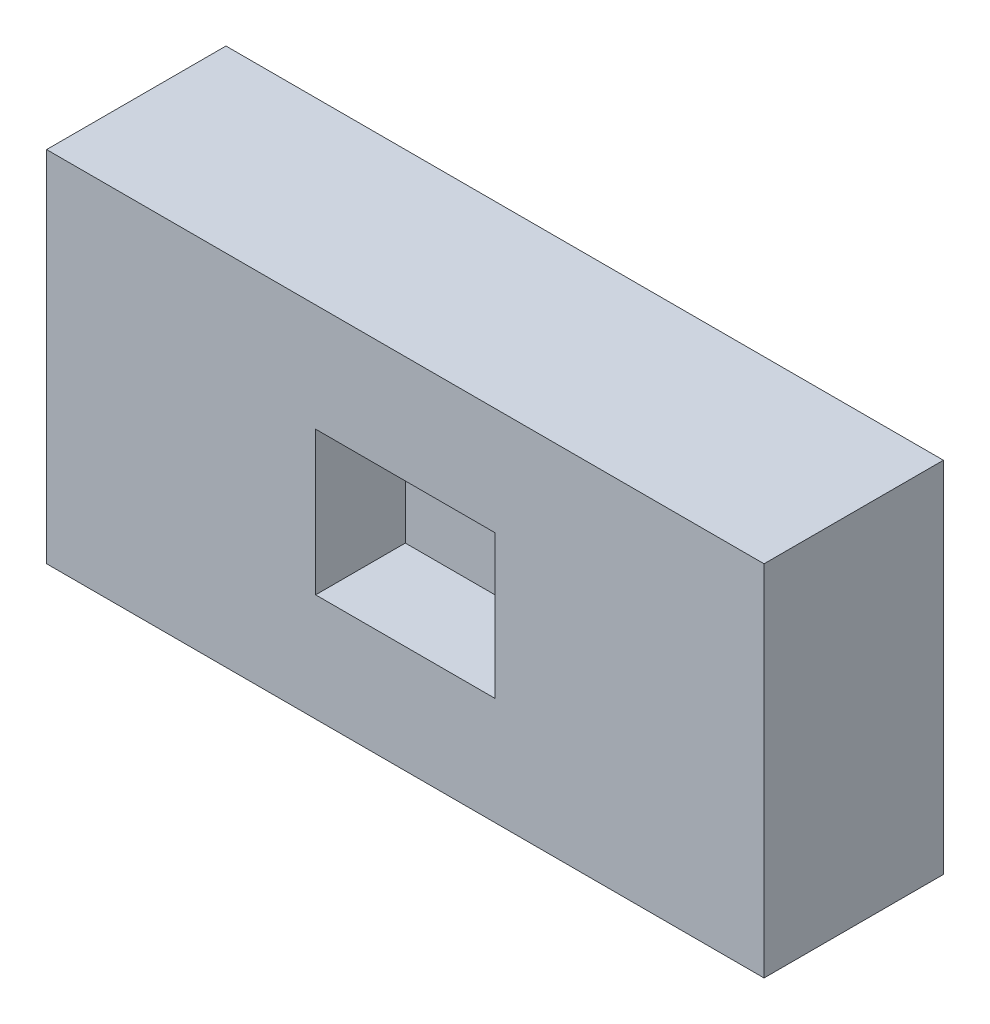
SolidWorks part; units mm, degrees
ref_plane "Front Plane" through (0, 0, 0) normal (0, 0, 1) x (1, 0, 0)
ref_plane "Top Plane" through (0, 0, 0) normal (0, 1, 0) x (1, 0, 0)
ref_plane "Right Plane" through (0, 0, 0) normal (1, 0, 0) x (0, 0, -1)
sketch "RectangleSketch" plane through (0, 0, 0) normal (0, 0, 1) x (1, 0, 0)
  line L1 (0, 0) -> (40, 0)
  line L2 (0, 0) -> (0, 20)
  line L3 (0, 20) -> (40, 20)
  line L4 (40, 0) -> (40, 20)
  dimension "width_mm" = 40
  dimension "height_mm" = 20
extrude "BlindBoss" add sketch "RectangleSketch" along normal blind 10 separate body
sketch "CutSketch" plane through (0, 0, 10) normal (0, 0, 1) x (1, 0, 0)
  line L1 (15, 6) -> (25, 6)
  line L2 (15, 6) -> (15, 14)
  line L3 (15, 14) -> (25, 14)
  line L4 (25, 6) -> (25, 14)
  dimension "cut_width_mm" = 10
  dimension "cut_height_mm" = 8
  dimension "cut_left_mm" = 15
  dimension "cut_bottom_mm" = 6
extrude "BlindCut" cut sketch "CutSketch" against normal blind 5
equation "\"cut_left_mm@CutSketch\" = (\"width_mm@RectangleSketch\" - \"cut_width_mm@CutSketch\") / 2"
equation "\"cut_bottom_mm@CutSketch\" = (\"height_mm@RectangleSketch\" - \"cut_height_mm@CutSketch\") / 2"
